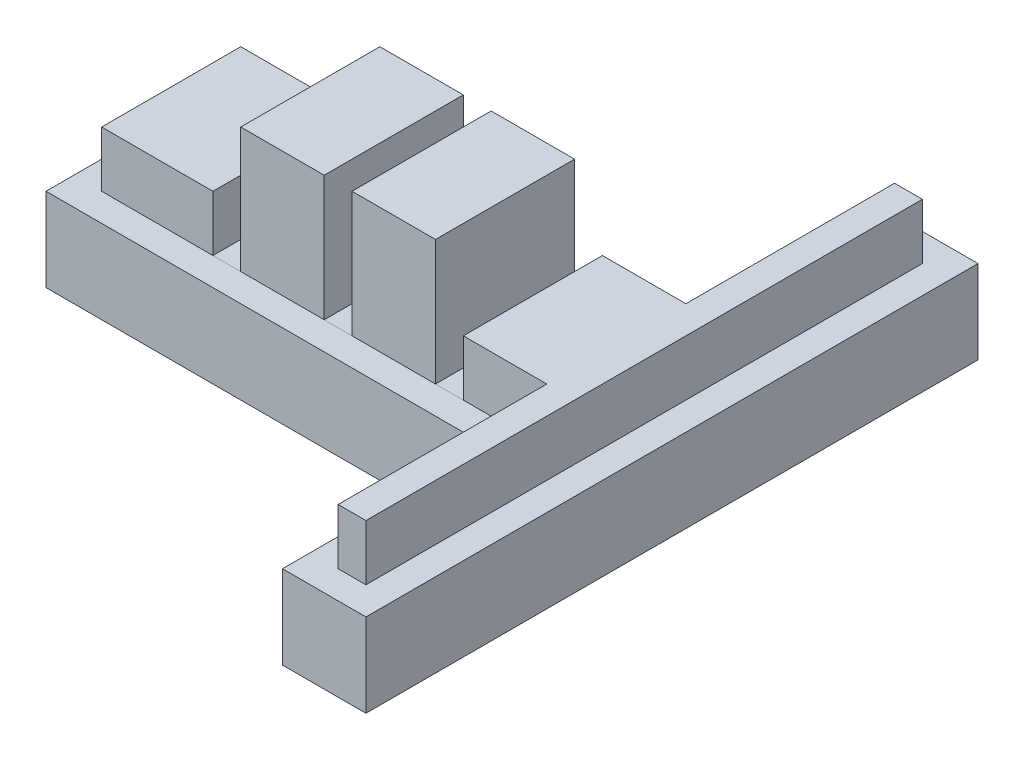
SolidWorks part; units mm, degrees
ref_plane "Front Plane" through (0, 0, 0) normal (0, 0, 1) x (1, 0, 0)
ref_plane "Top Plane" through (0, 0, 0) normal (0, 1, 0) x (1, 0, 0)
ref_plane "Right Plane" through (0, 0, 0) normal (1, 0, 0) x (0, 0, -1)
sketch "Sketch1" plane through (0, 0, 0) normal (0, 1, 0) x (1, 0, 0)
  line L1 (0, 0) -> (6, 0)
  line L2 (0, 0) -> (0, 10)
  line L3 (0, 10) -> (6, 10)
  line L4 (6, 0) -> (6, 10)
extrude "Boss-Extrude1" add sketch "Sketch1" along normal blind 13
sketch "Sketch2" plane through (0, 0, 0) normal (0, -1, 0) x (1, 0, 0)
  line L0 (6, 0) -> (6, -10) construction
  line L1 (5, -2) -> (1, -2)
  line L2 (5, -2) -> (5, -8)
  line L3 (5, -8) -> (1, -8)
  line L4 (1, -2) -> (1, -8)
  line L5 (0, -10) -> (0, 0) construction
  line L6 (0, 0) -> (6, 0) construction
  line L7 (6, -10) -> (0, -10) construction
  dimension "D1" = 1
  dimension "D2" = 1
  dimension "D3" = 2
  dimension "D4" = 2
extrude "Cut-Extrude1" cut sketch "Sketch2" against normal blind 11
sketch "Sketch3" plane through (0, 0, 0) normal (-1, 0, 0) x (0, 0, 1)
  line L0 (0, 13) -> (0, 0) construction
  line L1 (-10, 0) -> (0, 0)
  line L2 (-10, 0) -> (-10, 4)
  line L3 (-10, 4) -> (0, 4)
  line L4 (0, 0) -> (0, 4)
extrude "Boss-Extrude2" add sketch "Sketch3" along normal blind 2
pattern_linear "LPattern1" count 2 spacing 8 along (-1, 0, 0) of "Boss-Extrude2", "Boss-Extrude1", "Cut-Extrude1"
sketch "Sketch18" plane through (-10, 0, 0) normal (-1, 0, 0) x (0, 0, 1)
  line L1 (0, 0) -> (-10, 0)
  line L2 (0, 0) -> (0, 8)
  line L3 (0, 8) -> (-10, 8)
  line L4 (-10, 0) -> (-10, 8)
extrude "Boss-Extrude3" add sketch "Sketch18" along normal blind 8
sketch "Sketch20" plane through (6, 0, 0) normal (1, 0, 0) x (0, 0, -1)
  line L0 (10, 13) -> (10, 0) construction
  line L1 (0, 0) -> (10, 0)
  line L2 (0, 0) -> (0, 4)
  line L3 (0, 4) -> (10, 4)
  line L4 (10, 0) -> (10, 4)
extrude "Boss-Extrude4" add sketch "Sketch20" along normal blind 2
sketch "Sketch21" plane through (8, 0, 0) normal (1, 0, 0) x (0, 0, -1)
  line L1 (0, 0) -> (10, 0)
  line L2 (0, 0) -> (0, 8)
  line L3 (0, 8) -> (10, 8)
  line L4 (10, 0) -> (10, 8)
extrude "Boss-Extrude5" add sketch "Sketch21" along normal blind 6
sketch "Sketch22" plane through (14, 0, 0) normal (1, 0, 0) x (0, 0, -1)
  line L1 (0, 0) -> (10, 0) construction
  line L2 (0, 0) -> (0, 8) construction
  line L3 (0, 8) -> (10, 8) construction
  line L4 (10, 0) -> (10, 8) construction
  line L11 (25, 0) -> (25, 8)
  line L12 (-15, 8) -> (25, 8)
  line L13 (25, 0) -> (-15, 0)
  line L14 (-15, 0) -> (-15, 8)
  dimension "D1" = 15
  dimension "D2" = 15
extrude "Boss-Extrude6" add sketch "Sketch22" along normal blind 2
sketch "Sketch23" plane through (0, 0, 0) normal (0, -1, 0) x (1, 0, 0)
  line L0 (5, -8) -> (5, -2) construction
  line L1 (9, -2) -> (13, -2)
  line L2 (9, -2) -> (9, -8)
  line L3 (9, -8) -> (13, -8)
  line L4 (13, -2) -> (13, -8)
  line L5 (-2, 0) -> (14, 0) construction
  line L6 (-7, -2) -> (-7, -8) construction
  line L7 (-15, -2) -> (-11, -2)
  line L8 (-15, -2) -> (-15, -8)
  line L9 (-15, -8) -> (-11, -8)
  line L10 (-11, -2) -> (-11, -8)
  dimension "D1" = 4
  dimension "D2" = 2
  dimension "D3" = 4
extrude "Cut-Extrude2" cut sketch "Sketch23" against normal blind 6
combine bodies "Combine1" operation type add bodies to combine 135 136
sketch "Sketch33" plane through (0, 0, 0) normal (0, -1, 0) x (1, 0, 0)
  line L40 (14, 0) -> (-18, 0)
  line L41 (-18, 0) -> (-18, -10)
  line L42 (-18, -10) -> (14, -10)
  line L43 (14, -10) -> (14, -25)
  line L44 (14, -25) -> (16, -25)
  line L45 (16, -25) -> (16, 15)
  line L46 (16, 15) -> (14, 15)
  line L47 (14, 15) -> (14, 0)
  line L48 (14, 0) -> (-18, 0)
  line L49 (-18, 0) -> (-18, -10)
  line L50 (-18, -10) -> (14, -10)
  line L51 (14, -10) -> (14, -25)
  line L52 (14, -25) -> (16, -25)
  line L53 (16, -25) -> (16, 15)
  line L54 (16, 15) -> (14, 15)
  line L55 (14, 15) -> (14, 0)
  dimension "D2" = 0
extrude "Boss-Extrude15" add sketch "Sketch33" along normal blind 2 separate body contours L48 L49 L50 L51 L52 L53 L54 L55
sketch "Sketch34" plane through (0, -2, 0) normal (0, -1, 0) x (1, 0, 0)
  line L8 (12, 17) -> (12, 2)
  line L9 (12, 2) -> (-20, 2)
  line L10 (-20, 2) -> (-20, -12)
  line L11 (-20, -12) -> (12, -12)
  line L12 (12, -12) -> (12, -27)
  line L13 (12, -27) -> (18, -27)
  line L14 (18, -27) -> (18, 17)
  line L15 (18, 17) -> (12, 17)
  line L16 (14, 15) -> (14, 0)
  line L17 (14, 0) -> (-18, 0)
  line L18 (-18, 0) -> (-18, -10)
  line L19 (-18, -10) -> (14, -10)
  line L20 (14, -10) -> (14, -25)
  line L21 (14, -25) -> (16, -25)
  line L22 (16, -25) -> (16, 15)
  line L23 (16, 15) -> (14, 15)
  line L24 (14, 15) -> (14, 0)
  line L25 (14, 0) -> (-18, 0)
  line L26 (-18, 0) -> (-18, -10)
  line L27 (-18, -10) -> (14, -10)
  line L28 (14, -10) -> (14, -25)
  line L29 (14, -25) -> (16, -25)
  line L30 (16, -25) -> (16, 15)
  line L31 (16, 15) -> (14, 15)
  dimension "D1" = 0
  dimension "D2" = 2
extrude "Boss-Extrude16" add sketch "Sketch34" against normal blind 6
